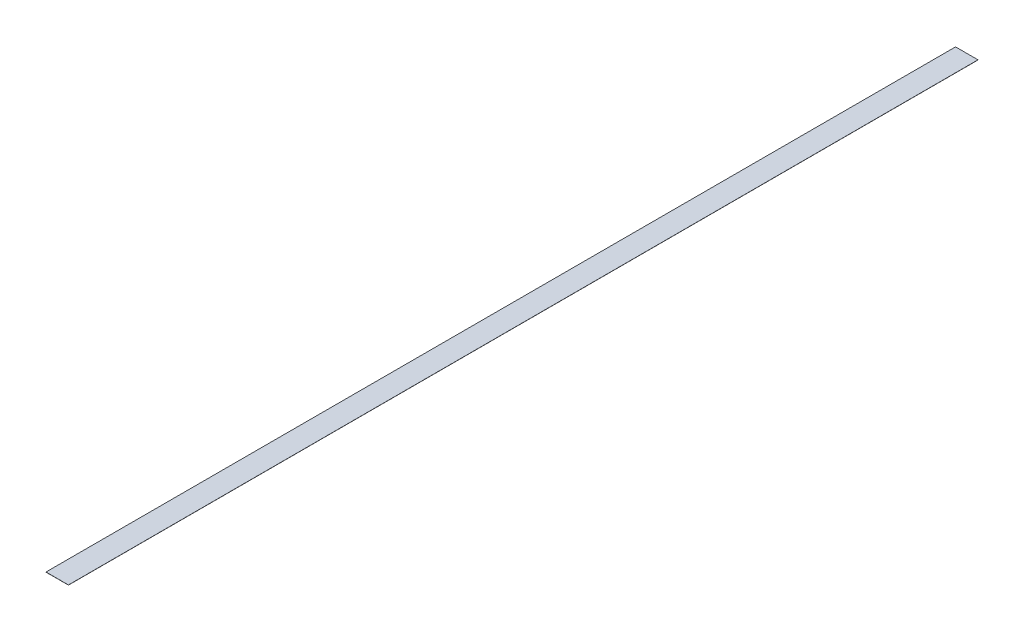
SolidWorks part; units mm, degrees
material "Kapton Film"
ref_plane "Front Plane" through (0, 0, 0) normal (0, 0, 1) x (1, 0, 0)
ref_plane "Top Plane" through (0, 0, 0) normal (0, 1, 0) x (1, 0, 0)
ref_plane "Right Plane" through (0, 0, 0) normal (1, 0, 0) x (0, 0, -1)
sketch "Sketch1" plane through (0, 0, 0) normal (0, 1, 0) x (1, 0, 0)
  line L5 (0, 0) -> (15, 0)
  line L6 (0, 0) -> (0, -608)
  line L7 (0, -608) -> (15, -608)
  line L8 (15, 0) -> (15, -608)
  dimension "D1" = 608
  dimension "D2" = 15
extrude "Boss-Extrude1" add sketch "Sketch1" along normal blind 0.1 contours L6 L7 L8 L5
sketch "Sketch2" plane through (0, 0.1, 0) normal (0, 1, 0) x (1, 0, 0)
  line L0 (0, -588) -> (15, -584.537) construction
  line L1 (0, 0) -> (0, -608) construction
  line L2 (15, 0) -> (15, -608) construction
  line L3 (5.0641, -586.8309) -> (5.0641, -558.2309) construction
  circle A0 centre (5.0641, -586.8309) radius 1
  circle A1 centre (9.9359, -585.7061) radius 1
  circle A2 centre (5.0641, -558.2309) radius 1
  circle A3 centre (9.9359, -557.1061) radius 1
  circle A4 centre (5.0641, -529.6309) radius 1
  circle A5 centre (9.9359, -528.5061) radius 1
  circle A6 centre (5.0641, -501.0309) radius 1
  circle A7 centre (9.9359, -499.9061) radius 1
  circle A8 centre (5.0641, -472.4309) radius 1
  circle A9 centre (9.9359, -471.3061) radius 1
  circle A10 centre (5.0641, -443.8309) radius 1
  circle A11 centre (9.9359, -442.7061) radius 1
  circle A12 centre (5.0641, -415.2309) radius 1
  circle A13 centre (9.9359, -414.1061) radius 1
  circle A14 centre (5.0641, -386.6309) radius 1
  circle A15 centre (9.9359, -385.5061) radius 1
  circle A16 centre (5.0641, -358.0309) radius 1
  circle A17 centre (9.9359, -356.9061) radius 1
  circle A18 centre (5.0641, -329.4309) radius 1
  circle A19 centre (9.9359, -328.3061) radius 1
  circle A20 centre (5.0641, -300.8309) radius 1
  circle A21 centre (9.9359, -299.7061) radius 1
  circle A22 centre (5.0641, -272.2309) radius 1
  circle A23 centre (9.9359, -271.1061) radius 1
  circle A24 centre (5.0641, -243.6309) radius 1
  circle A25 centre (9.9359, -242.5061) radius 1
  circle A26 centre (5.0641, -215.0309) radius 1
  circle A27 centre (9.9359, -213.9061) radius 1
  circle A28 centre (5.0641, -186.4309) radius 1
  circle A29 centre (9.9359, -185.3061) radius 1
  circle A30 centre (5.0641, -157.8309) radius 1
  circle A31 centre (9.9359, -156.7061) radius 1
  point P13 (7.5, -586.2685)
  dimension "D3" = 2
  dimension "D4" = 5
  dimension "D1" = 20
  dimension "D2" = 77
  dimension "D5" = 2.5
  dimension "D7" = 28.6
  dimension "D6" = 16
extrude "Cut-Extrude1" [suppressed] cut sketch "Sketch2" against normal through all
ref_plane "Plane1" through (7.5, 0, 0) normal (1, 0, 0) x (0, 0, -1)
sketch "Sketch3" [suppressed] plane through (0, 0.1, 0) normal (0, 1, 0) x (1, 0, 0)
  line L5 (15, 0) -> (15, -507) construction
  line L6 (0, 0) -> (15, 0)
  line L7 (0, 0) -> (0, -492)
  line L8 (0, -492) -> (15, -492)
  line L9 (15, 0) -> (15, -492)
  dimension "D1" = 15
extrude "Cut-Extrude2" [suppressed] cut sketch "Sketch3" against normal blind 10
